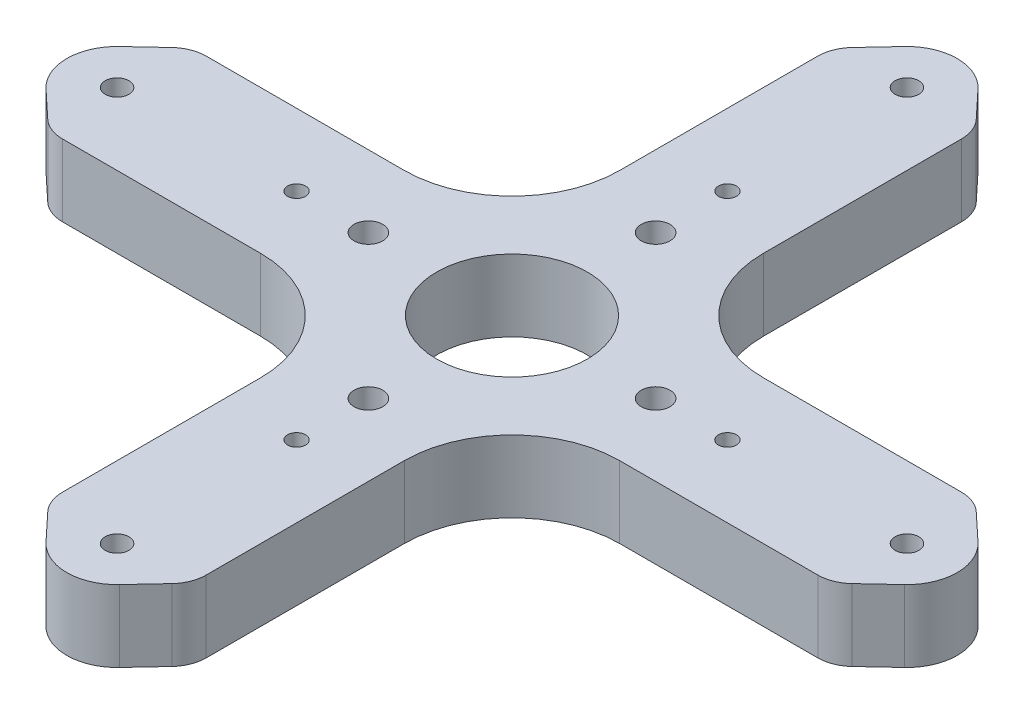
SolidWorks part; units mm, degrees
material "6063-T83"
ref_plane "Front Plane" through (0, 0, 0) normal (0, 0, 1) x (1, 0, 0)
ref_plane "Top Plane" through (0, 0, 0) normal (0, 1, 0) x (1, 0, 0)
ref_plane "Right Plane" through (0, 0, 0) normal (1, 0, 0) x (0, 0, -1)
sketch "Sketch1" plane through (0, 0, 0) normal (0, 1, 0) x (1, 0, 0)
  line L17 (10, 10) -> (54.5563, 10)
  line L18 (54.5563, 10) -> (59.7818, 5.1122)
  line L19 (10, -10) -> (54.5563, -10)
  line L20 (54.5563, -10) -> (59.7818, -5.1122)
  line L21 (55, 0) -> (0, 0) construction
  line L22 (54.5563, 10) -> (54.5563, -10) construction
  line L23 (10, -10) -> (10, -54.5563)
  line L24 (10, -54.5563) -> (5.1122, -59.7818)
  line L25 (-10, -54.5563) -> (-5.1122, -59.7818)
  line L26 (-10, -10) -> (-10, -54.5563)
  line L27 (-10, -10) -> (-54.5563, -10)
  line L28 (-54.5563, -10) -> (-59.7818, -5.1122)
  line L29 (-54.5563, 10) -> (-59.7818, 5.1122)
  line L30 (-10, 10) -> (-54.5563, 10)
  line L31 (-10, 10) -> (-10, 54.5563)
  line L32 (-10, 54.5563) -> (-5.1122, 59.7818)
  line L33 (10, 54.5563) -> (5.1122, 59.7818)
  line L34 (10, 10) -> (10, 54.5563)
  circle A0 centre (-20, 0) radius 2
  circle A1 centre (0, 20) radius 2
  circle A2 centre (20, 0) radius 2
  circle A3 centre (0, -20) radius 2
  circle A4 centre (0, 0) radius 10.5
  arc A5 (59.7818, 5.1122) -> (59.7818, -5.1122) centre (55, 0) cw
  circle A6 centre (0, 0) radius 60 construction
  arc A7 (5.1122, -59.7818) -> (-5.1122, -59.7818) centre (0, -55) cw
  arc A8 (-59.7818, -5.1122) -> (-59.7818, 5.1122) centre (-55, 0) cw
  arc A9 (-5.1122, 59.7818) -> (5.1122, 59.7818) centre (0, 55) cw
  point P30 (0, 0)
  point P49 (0, 0)
  dimension "D2" = 4
  dimension "D6" = 21
  dimension "D4" = 7
  dimension "D5" = 120
  dimension "D1" = 20
  dimension "D3" = 4
  dimension "D7" = 20
  dimension "D9" = 55
  dimension "D8" = 4
extrude "Boss-Extrude1" add sketch "Sketch1" along normal blind 10
fillet "Fillet1" radius 15 4 edges at (-10, 5, 10) (-10, 5, -10) (10, 5, -10) (10, 5, 10)
fillet "Fillet2" radius 5 8 edges at (-54.5563, 5, 10) (-54.5563, 5, -10) (-10, 5, -54.5563) (10, 5, -54.5563) (54.5563, 5, -10) (54.5563, 5, 10) (-10, 5, 54.5563) (10, 5, 54.5563)
hole_wizard "M4x0.7 Tapped Hole1" positions "Sketch2" profile "Sketch3" tap size "M4x0.7" standard "ANSI Metric" end condition through all
sketch "Sketch2" plane through (0, 0, 0) normal (0, -1, 0) x (-1, 0, 0)
  point P0 (0, -55)
  point P3 (-55, 0)
  point P6 (0, 55)
  point P9 (55, 0)
sketch "Sketch3" plane through (0, 0, 55) normal (1, 0, 0) x (0, 0, -1)
  line L0 (0, 0) -> (0, 10)
  line L1 (0, 10) -> (1.65, 10)
  line L2 (1.65, 10) -> (1.65, 0)
  line L5 (1.65, 0) -> (0, 0)
  line L11 (0, -6.35) -> (0, 107.95) construction
  dimension "Thru Tap Drill Dia." = 3.3
  dimension "Thru Tap Drill Depth" = 10
cosmetic thread "Hole Thread1" parameters "D2"=4
cosmetic thread "Hole Thread2" parameters "D2"=4
cosmetic thread "Hole Thread3" parameters "D2"=4
cosmetic thread "Hole Thread4" parameters "D2"=4
hole_wizard "M3x0.5 Tapped Hole1" positions "Sketch4" profile "Sketch5" tap size "M3x0.5" standard "ANSI Metric" end condition through all
sketch "Sketch4" plane through (0, 0, 0) normal (0, -1, 0) x (-1, 0, 0)
  line L0 (0, -55) -> (0, 0) construction
  point P0 (0, -30)
  point P15 (-30, 0)
  point P16 (0, 30)
  point P17 (30, 0)
  point P18 (0, 0)
  dimension "D1" = 30
  dimension "D2" = 4
sketch "Sketch5" plane through (0, 0, 30) normal (1, 0, 0) x (0, 0, -1)
  line L0 (0, 0) -> (0, 10)
  line L1 (0, 10) -> (1.25, 10)
  line L2 (1.25, 10) -> (1.25, 0)
  line L5 (1.25, 0) -> (0, 0)
  line L11 (0, -6.35) -> (0, 107.95) construction
  dimension "Thru Tap Drill Dia." = 2.5
  dimension "Thru Tap Drill Depth" = 10
cosmetic thread "Hole Thread5" parameters "D2"=3
cosmetic thread "Hole Thread6" parameters "D2"=3
cosmetic thread "Hole Thread7" parameters "D2"=3
cosmetic thread "Hole Thread8" parameters "D2"=3
